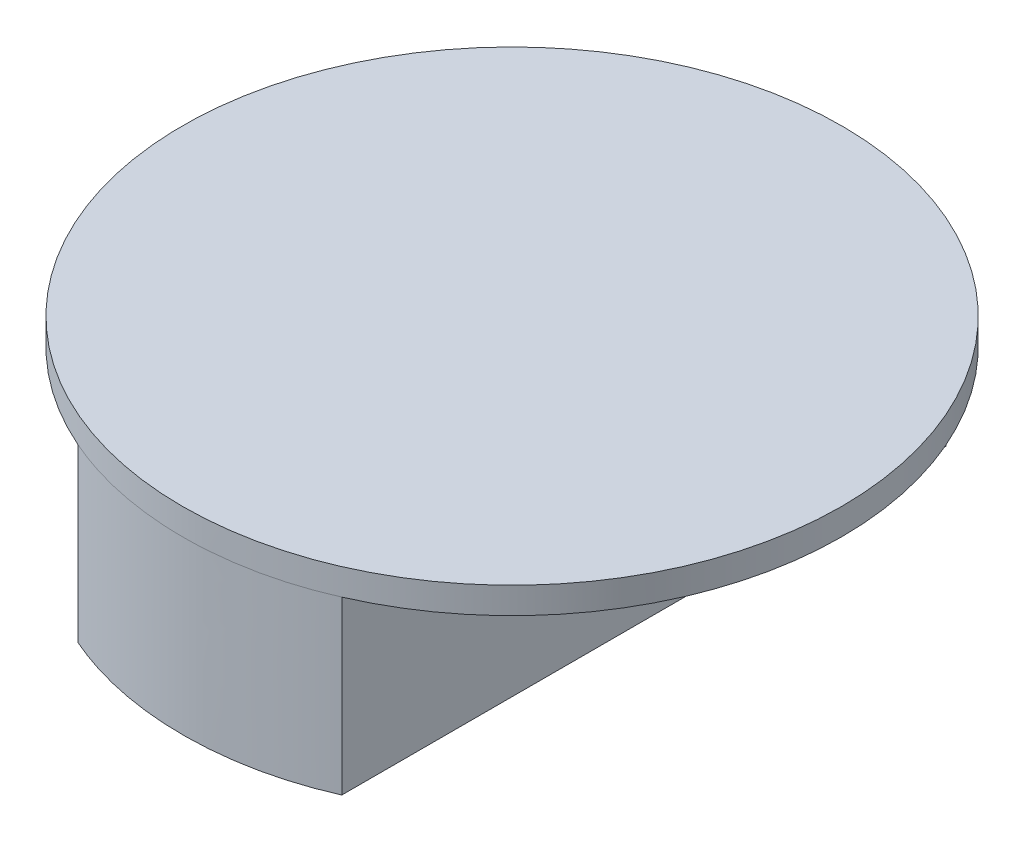
SolidWorks part; units mm, degrees
ref_plane "Front Plane" through (0, 0, 0) normal (0, 0, 1) x (1, 0, 0)
ref_plane "Top Plane" through (0, 0, 0) normal (0, 1, 0) x (1, 0, 0)
ref_plane "Right Plane" through (0, 0, 0) normal (1, 0, 0) x (0, 0, -1)
sketch "Sketch5" plane through (0, 0, 0) normal (0, 1, 0) x (1, 0, 0)
  circle A0 centre (0, 0) radius 6.35
  dimension "D1" = 12.7
extrude "Boss-Extrude4" add sketch "Sketch5" along normal blind 0.508
sketch "Sketch7" plane through (0, 0, 0) normal (0, -1, 0) x (1, 0, 0)
  line L0 (2.54, -5.8199) -> (2.54, 5.8199)
  line L2 (-2.54, 5.8199) -> (-2.54, -5.8199)
  circle A0 centre (0, 0) radius 6.35 construction
  spline S0 degree 3 poles (2.54, -5.8199) (0.947, -6.5307) (-0.9518, -6.5194) (-2.54, -5.8199) knots 0 0 0 0 1 1 1 1
  spline S1 degree 3 poles (2.54, 5.8199) (0.947, 6.5307) (-0.9518, 6.5194) (-2.54, 5.8199) knots 0 0 0 0 1 1 1 1
  dimension "D1" = 5.08
extrude "Boss-Extrude8" add sketch "Sketch7" along normal blind 3.302
